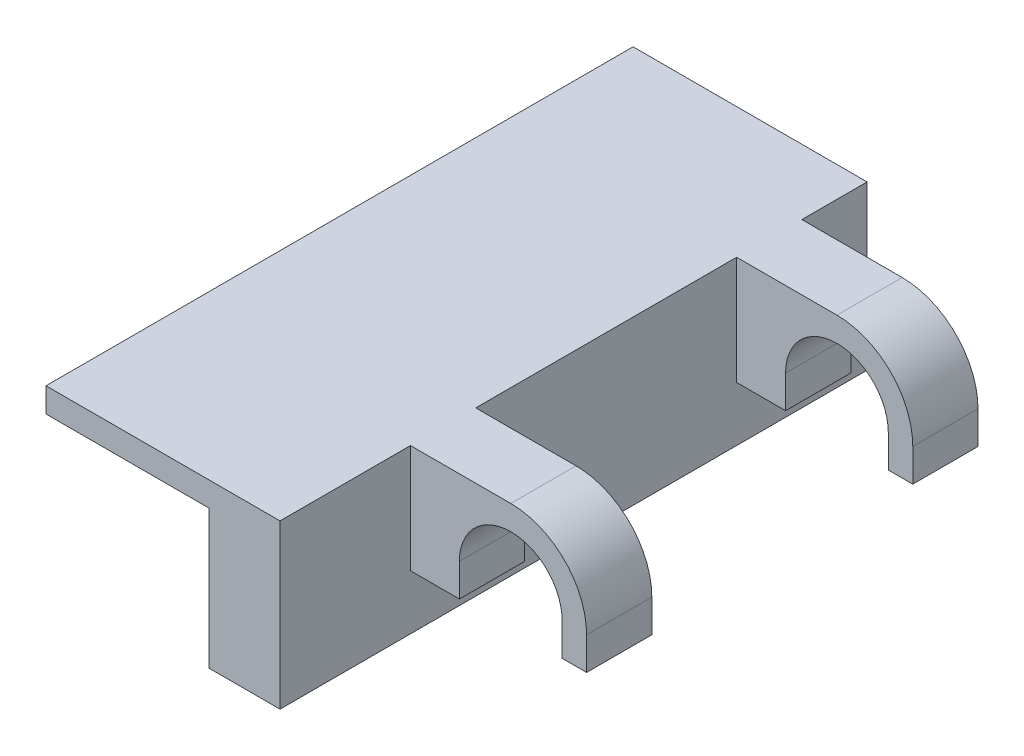
SolidWorks part; units mm, degrees
ref_plane "Ebene vorne" through (0, 0, 0) normal (0, 0, 1) x (1, 0, 0)
ref_plane "Ebene oben" through (0, 0, 0) normal (0, 1, 0) x (1, 0, 0)
ref_plane "Ebene rechts" through (0, 0, 0) normal (1, 0, 0) x (0, 0, -1)
sketch "Skizze1" plane through (0, 0, 0) normal (0, 0, 1) x (1, 0, 0)
  line L0 (-195, 0) -> (195, 0) construction
  line L1 (-198.15, 0) -> (-198.15, -2)
  line L2 (-191.85, 0) -> (-191.85, -2)
  line L3 (-188.85, -5.35) -> (188.85, -5.35)
  line L4 (-198.15, -2) -> (-199.65, -2)
  line L5 (-199.65, -2) -> (-199.65, 0)
  line L6 (-195, 4.65) -> (195, 4.65)
  line L7 (0, 4.65) -> (0, -5.35) construction
  line L8 (-191.85, -2) -> (-188.85, -2)
  line L9 (-188.85, -2) -> (-188.85, -5.35)
  line L10 (188.85, -2) -> (188.85, -5.35)
  line L11 (191.85, -2) -> (188.85, -2)
  line L12 (199.65, -2) -> (199.65, 0)
  line L13 (198.15, -2) -> (199.65, -2)
  line L14 (191.85, 0) -> (191.85, -2)
  line L15 (198.15, 0) -> (198.15, -2)
  arc A0 (-198.15, 0) -> (-191.85, 0) centre (-195, 0) cw
  arc A1 (-199.65, 0) -> (-195, 4.65) centre (-195, 0) cw
  arc A2 (199.65, 0) -> (195, 4.65) centre (195, 0) ccw
  arc A3 (198.15, 0) -> (191.85, 0) centre (195, 0) ccw
  point P3 (0, 0)
  dimension "D2" = 3.15
  dimension "D1" = 390
  dimension "D3" = 1.5
  dimension "D4" = 2
  dimension "D5" = 10
  dimension "D6" = 3
extrude "Aufsatz-Linear austragen2" add sketch "Skizze1" along normal mid plane 36
sketch "Skizze3" plane through (0, -5.35, 0) normal (0, -1, 0) x (1, 0, 0)
  line L0 (-188.85, 18) -> (-188.85, -18) construction
  line L1 (-199.65, 18) -> (-188.85, 18)
  line L2 (-199.65, 18) -> (-199.65, 14)
  line L3 (-199.65, 14) -> (-188.85, 14)
  line L4 (-188.85, 18) -> (-188.85, 14)
  line L5 (-199.65, 18) -> (-199.65, -18) construction
  line L6 (-199.65, 10) -> (-188.85, 10)
  line L7 (-199.65, 10) -> (-199.65, -6)
  line L8 (-199.65, -6) -> (-188.85, -6)
  line L9 (-188.85, 10) -> (-188.85, -6)
  line L10 (-188.85, 18) -> (-188.85, -18) construction
  line L11 (199.65, 18) -> (199.65, -18) construction
  line L12 (-199.65, -18) -> (-188.85, -18)
  line L13 (-199.65, -18) -> (-199.65, -10)
  line L14 (-199.65, -10) -> (-188.85, -10)
  line L15 (-188.85, -18) -> (-188.85, -10)
  line L16 (188.85, 18) -> (199.65, 18)
  line L17 (188.85, 18) -> (188.85, 10)
  line L18 (188.85, 10) -> (199.65, 10)
  line L19 (199.65, 18) -> (199.65, 10)
  line L20 (188.85, 18) -> (188.85, -18) construction
  line L21 (188.85, 6) -> (199.65, 6)
  line L22 (188.85, 6) -> (188.85, -10)
  line L23 (188.85, -10) -> (199.65, -10)
  line L24 (199.65, 6) -> (199.65, -10)
  line L26 (188.85, -14) -> (199.65, -14)
  line L27 (188.85, -14) -> (188.85, -18)
  line L28 (188.85, -18) -> (199.65, -18)
  line L29 (199.65, -14) -> (199.65, -18)
  dimension "D1" = 4
  dimension "D2" = 4
  dimension "D3" = 4
  dimension "D4" = 8
  dimension "D5" = 4
  dimension "D6" = 4
extrude "Schnitt-Linear austragen1" cut sketch "Skizze3" against normal through all
sketch "Skizze4" plane through (0, 0, 18) normal (0, 0, 1) x (1, 0, 0)
  line L0 (174.5, 4.65) -> (174.5, 3.15)
  line L1 (188.85, 4.65) -> (-188.85, 4.65) construction
  line L2 (174.5, 3.15) -> (184.5, 3.15)
  line L3 (184.5, 3.15) -> (184.5, -5.35)
  line L4 (-188.85, -5.35) -> (188.85, -5.35) construction
  line L5 (184.5, -5.35) -> (-199.65, -5.35)
  line L6 (-199.65, -5.35) -> (-199.65, 4.65)
  line L7 (-199.65, 4.65) -> (174.5, 4.65)
  line L8 (-199.65, 0) -> (-199.65, -2) construction
  line L10 (0, 4.65) -> (0, -5.35) construction
  dimension "D1" = 369
  dimension "D2" = 1.5
  dimension "D3" = 10
extrude "Schnitt-Linear austragen2" cut sketch "Skizze4" against normal through all
